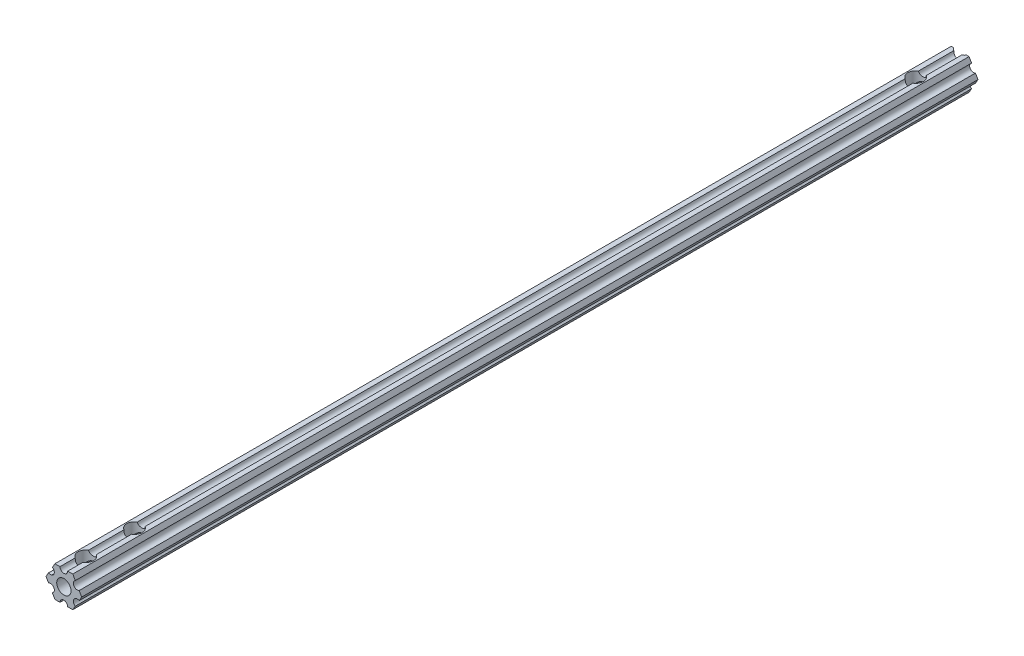
SolidWorks part; units mm, degrees
material "6061-T6 (SS)"
ref_plane "Alzado" through (0, 0, 0) normal (0, 0, 1) x (1, 0, 0)
ref_plane "Planta" through (0, 0, 0) normal (0, 1, 0) x (1, 0, 0)
ref_plane "Vista lateral" through (0, 0, 0) normal (1, 0, 0) x (0, 0, -1)
sketch "Croquis1" plane through (0, 0, 0) normal (0, 0, 1) x (1, 0, 0)
  line L24 (620.4484, 354.8104) -> (619.409, 356.6106)
  line L25 (619.409, 356.6106) -> (617.3304, 356.6106)
  line L26 (614.1554, 356.6106) -> (612.0767, 356.6106)
  line L27 (612.0767, 356.6106) -> (611.0374, 354.8104)
  line L28 (609.4499, 352.0608) -> (608.4105, 350.2606)
  line L29 (608.4105, 350.2606) -> (609.4499, 348.4604)
  line L30 (611.0374, 345.7108) -> (612.0767, 343.9106)
  line L31 (612.0767, 343.9106) -> (614.1554, 343.9106)
  line L32 (617.3304, 343.9106) -> (619.409, 343.9106)
  line L33 (619.409, 343.9106) -> (620.4484, 345.7108)
  line L34 (622.0359, 348.4604) -> (623.0752, 350.2606)
  line L35 (623.0752, 350.2606) -> (622.0359, 352.0608)
  arc A2 (614.276, 347.72) -> (617.2097, 352.8013) centre (615.7429, 350.2606) ccw
  arc A3 (617.2097, 352.8013) -> (614.276, 347.72) centre (615.7429, 350.2606) ccw
  arc A16 (614.9491, 355.2358) -> (617.3304, 356.6106) centre (615.7429, 356.6106) ccw
  arc A17 (614.1554, 356.6106) -> (614.9491, 355.2358) centre (615.7429, 356.6106) ccw
  arc A18 (609.4499, 352.0608) -> (611.0374, 354.8104) centre (610.2436, 353.4356) ccw
  arc A19 (611.0374, 345.7108) -> (609.4499, 348.4604) centre (610.2436, 347.0856) ccw
  arc A20 (617.3304, 343.9106) -> (614.1554, 343.9106) centre (615.7429, 343.9106) ccw
  arc A21 (622.0359, 348.4604) -> (620.4484, 345.7108) centre (621.2421, 347.0856) ccw
  arc A22 (620.4484, 352.0608) -> (622.0359, 352.0608) centre (621.2421, 353.4356) ccw
  arc A23 (620.4484, 354.8104) -> (620.4484, 352.0608) centre (621.2421, 353.4356) ccw
extrude "Saliente-Extruir1" add sketch "Croquis1" against normal blind 368
sketch "Croquis2" plane through (0, 356.6106, 0) normal (0, 1, 0) x (1, 0, 0)
  circle A0 centre (615.7429, 349.7499) radius 3.175
  circle A1 centre (615.7429, 369.7499) radius 3.175
  circle A2 centre (615.7429, 29) radius 3.175
  circle A3 centre (615.7429, 9) radius 3.175
extrude "Cortar-Extruir1" cut sketch "Croquis2" against normal through all
